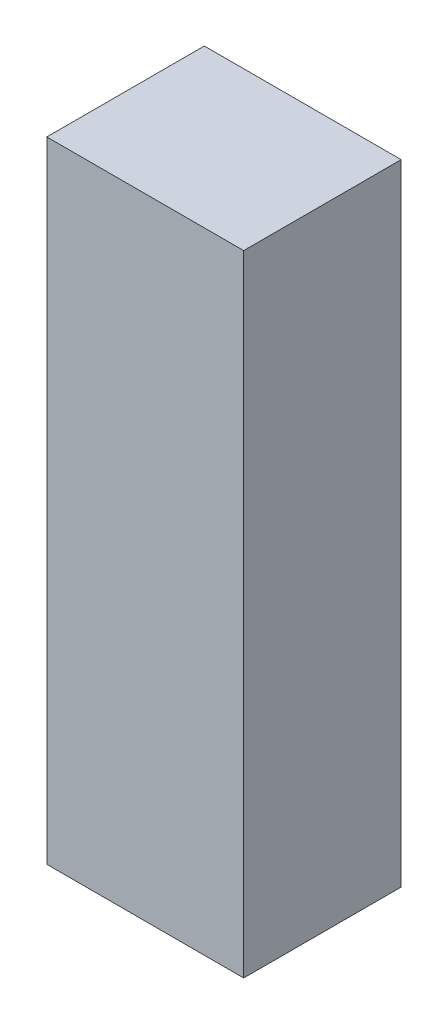
SolidWorks part; units mm, degrees
ref_plane "Front Plane" through (0, 0, 0) normal (0, 0, 1) x (1, 0, 0)
ref_plane "Top Plane" through (0, 0, 0) normal (0, 1, 0) x (1, 0, 0)
ref_plane "Right Plane" through (0, 0, 0) normal (1, 0, 0) x (0, 0, -1)
sketch "Sketch1" plane through (0, 0, 0) normal (0, 0, 1) x (1, 0, 0)
  line L1 (0, 0) -> (0.25, 0)
  line L2 (0, 0) -> (0, 0.8)
  line L3 (0, 0.8) -> (0.25, 0.8)
  line L4 (0.25, 0) -> (0.25, 0.8)
  dimension "D1" = 0.25
  dimension "D2" = 0.8
extrude "Boss-Extrude1" add sketch "Sketch1" along normal blind 0.2 contours L2 L3 L4 L1
equation "\"t\"= 0.25'thickness of the sheets"
equation "\"t_cf\" = 0.115'thickness of single carbon fiber layer"
equation "\"t_kapton\" = 0.025'thickness of single Kapton flex layer"
equation "\"t_fr4\" = 0.1'thickness of FR4 with copper layer"
equation "\"joint_flex\"= 0.1'Width of flextures gap"
equation "\"joint_flex_eff\"= 0.02'Width of flecture after castelation"
equation "\"joint_fold\"= 0.2'Width of folding joints for 90deg fold"
equation "\"gap_tolerance\"= 0.002'Width to have interfecence fit between carbon fiber inserts"
equation "\"assemble_angle\"= 90'Angle of assembly parts"
equation "\"link_lift\"= 0.5'Actuation linkage amplification for the lift motion"
equation "\"link_swing\"= 0.45'Actuation linkage amplification for the swing motion"
equation "\"D1@Sketch1\"=\"t\""
equation "\"D1@Boss-Extrude1\"=\"joint_fold\""
